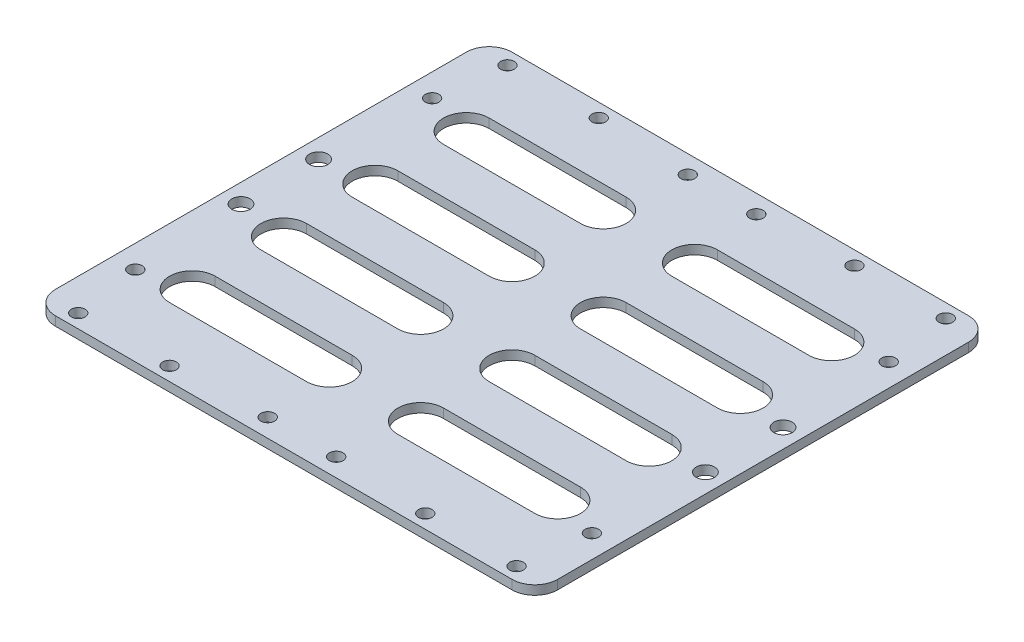
SolidWorks part; units mm, degrees
ref_plane "前视基准面" through (0, 0, 0) normal (0, 0, 1) x (1, 0, 0)
ref_plane "上视基准面" through (0, 0, 0) normal (0, 1, 0) x (1, 0, 0)
ref_plane "右视基准面" through (0, 0, 0) normal (1, 0, 0) x (0, 0, -1)
other "Configuration Table"
sketch "草图1" plane through (0, 0, 0) normal (0, 1, 0) x (1, 0, 0)
  line L0 (-48, -47) -> (-28, -47) construction
  line L2 (-55, 50) -> (-55, -50)
  line L3 (-55, -50) -> (55, -50)
  line L4 (55, 50) -> (55, -50)
  line L5 (-55, 50) -> (55, -50) construction
  line L6 (-55, -50) -> (55, 50) construction
  line L7 (0, 0) -> (0, -50) construction
  line L8 (-50.8546, 8.5) -> (-50.8546, -8.5) construction
  line L9 (-50.8546, 0) -> (0, 0) construction
  line L10 (-48, 47) -> (-28, 47) construction
  line L11 (-55, 50) -> (55, 50)
  line L12 (48, -47) -> (28, -47) construction
  line L13 (48, 47) -> (28, 47) construction
  line L14 (50.8546, 8.5) -> (50.8546, -8.5) construction
  circle A0 centre (-48, -47) radius 1.5
  circle A1 centre (-28, -47) radius 1.5
  circle A4 centre (-50.8546, 8.5) radius 2
  circle A5 centre (-50.8546, -8.5) radius 2
  circle A6 centre (-28, 47) radius 1.5
  circle A7 centre (-48, 47) radius 1.5
  circle A8 centre (28, -47) radius 1.5
  circle A9 centre (48, -47) radius 1.5
  circle A10 centre (48, 47) radius 1.5
  circle A11 centre (28, 47) radius 1.5
  circle A12 centre (50.8546, -8.5) radius 2
  circle A13 centre (50.8546, 8.5) radius 2
  point P0 (0, 0)
  dimension "D2" = 3
  dimension "D8" = 4
  dimension "D1" = 20
  dimension "D3" = 3
  dimension "D4" = 28
  dimension "D5" = 110
  dimension "D6" = 100
  dimension "D7" = 17
  dimension "D9" = 4.1454
extrude "凸台-拉伸1" add sketch "草图1" along normal blind 2
fillet "圆角1" radius 5 4 edges at (55, 1, 50) (-55, 1, 50) (55, 1, -50) (-55, 1, -50)
sketch "草图2" plane through (0, 2, 0) normal (0, 1, 0) x (1, 0, 0)
  line L0 (0, 0) -> (0, -50) construction
  line L2 (-40, 30) -> (-10, 30) construction
  line L3 (-40, 35) -> (-10, 35)
  line L4 (-40, 25) -> (-10, 25)
  line L5 (-40, 10) -> (-10, 10) construction
  line L6 (-40, 15) -> (-10, 15)
  line L7 (-40, 5) -> (-10, 5)
  line L8 (-40, -10) -> (-10, -10) construction
  line L9 (-40, -5) -> (-10, -5)
  line L10 (-40, -15) -> (-10, -15)
  line L11 (-40, -30) -> (-10, -30) construction
  line L12 (-40, -25) -> (-10, -25)
  line L13 (-40, -35) -> (-10, -35)
  line L14 (-50, -50) -> (50, -50) construction
  line L15 (0, 0) -> (-55, 0) construction
  line L16 (-55, 45) -> (-55, -45) construction
  line L17 (40, 30) -> (10, 30) construction
  line L18 (40, 35) -> (10, 35)
  line L19 (40, 25) -> (10, 25)
  line L20 (40, 10) -> (10, 10) construction
  line L21 (40, 15) -> (10, 15)
  line L22 (40, 5) -> (10, 5)
  line L23 (40, -10) -> (10, -10) construction
  line L24 (40, -5) -> (10, -5)
  line L25 (40, -15) -> (10, -15)
  line L26 (40, -30) -> (10, -30) construction
  line L27 (40, -25) -> (10, -25)
  line L28 (40, -35) -> (10, -35)
  arc A0 (-40, 35) -> (-40, 25) centre (-40, 30) ccw
  arc A1 (-10, 25) -> (-10, 35) centre (-10, 30) ccw
  arc A2 (-40, 15) -> (-40, 5) centre (-40, 10) ccw
  arc A3 (-10, 5) -> (-10, 15) centre (-10, 10) ccw
  arc A4 (-40, -5) -> (-40, -15) centre (-40, -10) ccw
  arc A5 (-10, -15) -> (-10, -5) centre (-10, -10) ccw
  arc A6 (-40, -25) -> (-40, -35) centre (-40, -30) ccw
  arc A7 (-10, -35) -> (-10, -25) centre (-10, -30) ccw
  arc A8 (40, 35) -> (40, 25) centre (40, 30) cw
  arc A9 (10, 25) -> (10, 35) centre (10, 30) cw
  arc A10 (40, 15) -> (40, 5) centre (40, 10) cw
  arc A11 (10, 5) -> (10, 15) centre (10, 10) cw
  arc A12 (40, -5) -> (40, -15) centre (40, -10) cw
  arc A13 (10, -15) -> (10, -5) centre (10, -10) cw
  arc A14 (40, -25) -> (40, -35) centre (40, -30) cw
  arc A15 (10, -35) -> (10, -25) centre (10, -30) cw
  point P7 (-25, 30)
  point P16 (-25, 10)
  point P23 (-25, -10)
  point P30 (-25, -30)
  point P38 (25, 30)
  point P45 (25, 10)
  point P52 (25, -10)
  point P59 (25, -30)
  dimension "D1" = 5
  dimension "D2" = 30
  dimension "D3" = 10
  dimension "D5" = 10
  dimension "D4" = 4
extrude "减重" cut sketch "草图2" against normal blind 10
sketch "草图3" plane through (0, 2, 0) normal (0, 1, 0) x (1, 0, 0)
  line L0 (-7.5, 46) -> (7.5, 46) construction
  line L1 (0, 0) -> (0, 46) construction
  line L2 (0, 0) -> (55, 0) construction
  line L3 (55, 45) -> (55, -45) construction
  line L4 (-50, 50) -> (50, 50) construction
  circle A0 centre (-7.5, 46) radius 1.5
  circle A1 centre (7.5, 46) radius 1.5
  circle A2 centre (-7.5, -46) radius 1.5
  circle A3 centre (7.5, -46) radius 1.5
  dimension "D3" = 3
  dimension "D1" = 15
  dimension "D2" = 4
extrude "碰珠锁安装孔" cut sketch "草图3" against normal blind 10
sketch "草图4" plane through (0, 2, 0) normal (0, 1, 0) x (1, 0, 0)
  line L0 (-50, -50) -> (50, -50) construction
  line L1 (0, 0) -> (0, -50) construction
  line L2 (0, 0) -> (55, 0) construction
  line L3 (55, 45) -> (55, -45) construction
  line L4 (-55, 45) -> (-55, -45) construction
  circle A0 centre (-50, -32.5) radius 1.5
  circle A1 centre (50, -32.5) radius 1.5
  circle A2 centre (50, 32.5) radius 1.5
  circle A3 centre (-50, 32.5) radius 1.5
  point P7 (55, 0)
  dimension "D3" = 3
  dimension "D1" = 17.5
  dimension "D2" = 5
extrude "裙边安装孔" cut sketch "草图4" against normal blind 10
